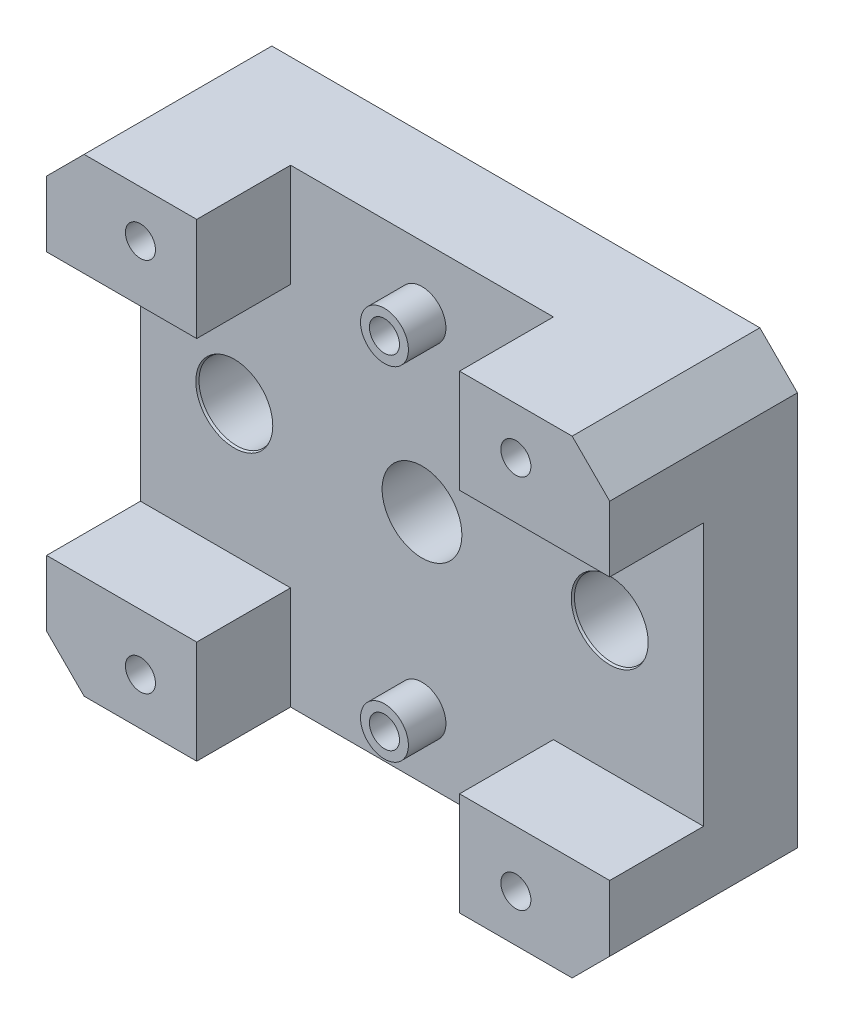
SolidWorks part; units mm, degrees
ref_plane "前视基准面" through (0, 0, 0) normal (0, 0, 1) x (1, 0, 0)
ref_plane "上视基准面" through (0, 0, 0) normal (0, 1, 0) x (1, 0, 0)
ref_plane "右视基准面" through (0, 0, 0) normal (1, 0, 0) x (0, 0, -1)
other "Configuration Table"
sketch "草图1" plane through (0, 0, 0) normal (0, 0, 1) x (1, 0, 0)
  line L1 (-30, -25) -> (30, -25)
  line L2 (-30, -25) -> (-30, 25)
  line L3 (-30, 25) -> (30, 25)
  line L4 (30, -25) -> (30, 25)
  line L5 (-30, -25) -> (30, 25) construction
  line L6 (-30, 25) -> (30, -25) construction
  point P0 (0, 0)
  dimension "D1" = 50
  dimension "D2" = 60
extrude "凸台-拉伸1" add sketch "草图1" along normal blind 10
hole_wizard "孔1" positions "草图2" profile "草图3" legacy
sketch "草图2" plane through (0, 0, 10) normal (0, 0, 1) x (1, 0, 0)
  point P0 (0, 0)
sketch "草图3" plane through (0, 0, 10) normal (1, 0, 0) x (0, -1, 0)
  line L0 (0, 0) -> (0, 20)
  line L1 (0, 20) -> (4.25, 20)
  line L2 (4.25, 20) -> (4.25, 0)
  line L3 (4.25, 0) -> (0, 0)
  line L4 (0, 110) -> (0, -10) construction
  dimension "直径" = 8.5
  dimension "深度" = 20
hole_wizard "孔2" positions "草图4" profile "草图5" legacy end condition through all
sketch "草图4" plane through (0, 0, 10) normal (0, 0, 1) x (1, 0, 0)
  point P0 (20, 0)
  point P2 (-20, 0)
  dimension "D1" = 20
  dimension "D2" = 20
sketch "草图5" plane through (20, 0, 10) normal (1, 0, 0) x (0, -1, 0)
  line L0 (0, 0) -> (0, 10)
  line L1 (0, 10) -> (4, 10)
  line L2 (4, 10) -> (4, 0.2414)
  line L3 (4, 0.2414) -> (4.1, 0)
  line L4 (4.1, 0) -> (0, 0)
  line L5 (0, -6.4453) -> (0, 115.525) construction
  line L6 (-4, 0.2414) -> (-4.1, 0) construction
  dimension "直径" = 8
  dimension "深度" = 10
  dimension "锥坑角度" = 45
  dimension "锥坑直径" = 8.2
sketch "草图9" plane through (0, 0, 10) normal (0, 0, 1) x (1, 0, 0)
  circle A0 centre (0, 18.25) radius 2.55
  circle A1 centre (0, -18.25) radius 2.55
  dimension "D1" = 5.1
  dimension "D2" = 5.1
  dimension "D3" = 18.25
  dimension "D4" = 18.25
extrude "凸台-拉伸3" add sketch "草图9" along normal blind 4
hole_wizard "孔3" positions "草图10" profile "草图11" legacy end condition through all
sketch "草图10" plane through (0, 0, 14) normal (0, 0, 1) x (1, 0, 0)
  point P0 (0, 18.25)
  point P3 (0, -18.25)
sketch "草图11" plane through (0, 18.25, 14) normal (1, 0, 0) x (0, -1, 0)
  line L0 (0, 0) -> (0, 14)
  line L1 (0, 14) -> (1.6, 14)
  line L2 (1.6, 14) -> (1.6, 0)
  line L3 (1.6, 0) -> (0, 0)
  line L4 (0, 110) -> (0, -10) construction
  dimension "直径" = 3.2
  dimension "深度" = 14
sketch "草图15" plane through (0, 0, 10) normal (0, 0, 1) x (1, 0, 0)
  line L0 (-30, 0) -> (30, 0)
  line L1 (-30, 25) -> (-30, -25) construction
  line L2 (30, -25) -> (30, 25) construction
  line L3 (0, 25) -> (0, -25)
  line L4 (30, 25) -> (-30, 25) construction
  line L5 (-30, -25) -> (30, -25) construction
  line L6 (0, 0) -> (-29.5019, 29.5019)
  line L8 (30, 14.0027) -> (14.0027, 14.0027)
  line L9 (-30, 25) -> (-14.0027, 25)
  line L10 (-30, 25) -> (-30, 14.0027)
  line L11 (-30, 14.0027) -> (-14.0027, 14.0027)
  line L12 (-14.0027, 25) -> (-14.0027, 14.0027)
  line L13 (14.0027, 25) -> (14.0027, 14.0027)
  line L14 (30, 25) -> (14.0027, 25)
  line L15 (30, 25) -> (30, 14.0027)
  line L16 (-30, -14.0027) -> (-14.0027, -14.0027)
  line L17 (-14.0027, -25) -> (-14.0027, -14.0027)
  line L18 (-30, -25) -> (-14.0027, -25)
  line L19 (-30, -25) -> (-30, -14.0027)
  line L20 (30, -25) -> (30, -14.0027)
  line L21 (30, -25) -> (14.0027, -25)
  line L22 (14.0027, -25) -> (14.0027, -14.0027)
  line L23 (30, -14.0027) -> (14.0027, -14.0027)
  circle A0 centre (-20, 20) radius 1.6
  circle A1 centre (20, 20) radius 1.6
  circle A2 centre (20, -20) radius 1.6
  circle A3 centre (-20, -20) radius 1.6
  line M11 (30, -25) -> (30, 25)
  line M12 (30, 25) -> (-30, 25)
  line M13 (-30, 25) -> (-30, -25)
  line M14 (-30, -25) -> (30, -25)
  dimension "D3" = 3.2
  dimension "D1" = 45
  dimension "D2" = 40
extrude "凸台-拉伸4" add sketch "草图15" along normal blind 10 contours A0 L6 L11 M12 M13 | A0 L6 L12 M12 | L13 L8 A1 M12 M11 | L23 L22 A2 M11 M14 | L17 L16 A3 M14 M13
hole_wizard "孔4" positions "草图16" profile "草图17" legacy end condition through all
sketch "草图16" plane through (0, 0, 10) normal (0, 0, 1) x (1, 0, 0)
  point P2 (-20, 20)
  point P5 (20, 20)
  point P8 (20, -20)
  point P11 (-20, -20)
sketch "草图17" plane through (-20, 20, 10) normal (1, 0, 0) x (0, -1, 0)
  line L0 (0, 0) -> (0, 10)
  line L1 (0, 10) -> (1.6, 10)
  line L2 (1.6, 10) -> (1.6, 0)
  line L3 (1.6, 0) -> (0, 0)
  line L4 (0, 110) -> (0, -10) construction
  dimension "直径" = 3.2
  dimension "深度" = 10
chamfer "倒角1" distance 4 angle 45 4 edges at (30, -25, 10) (-30, -25, 10) (-30, 25, 10) (30, 25, 10)
